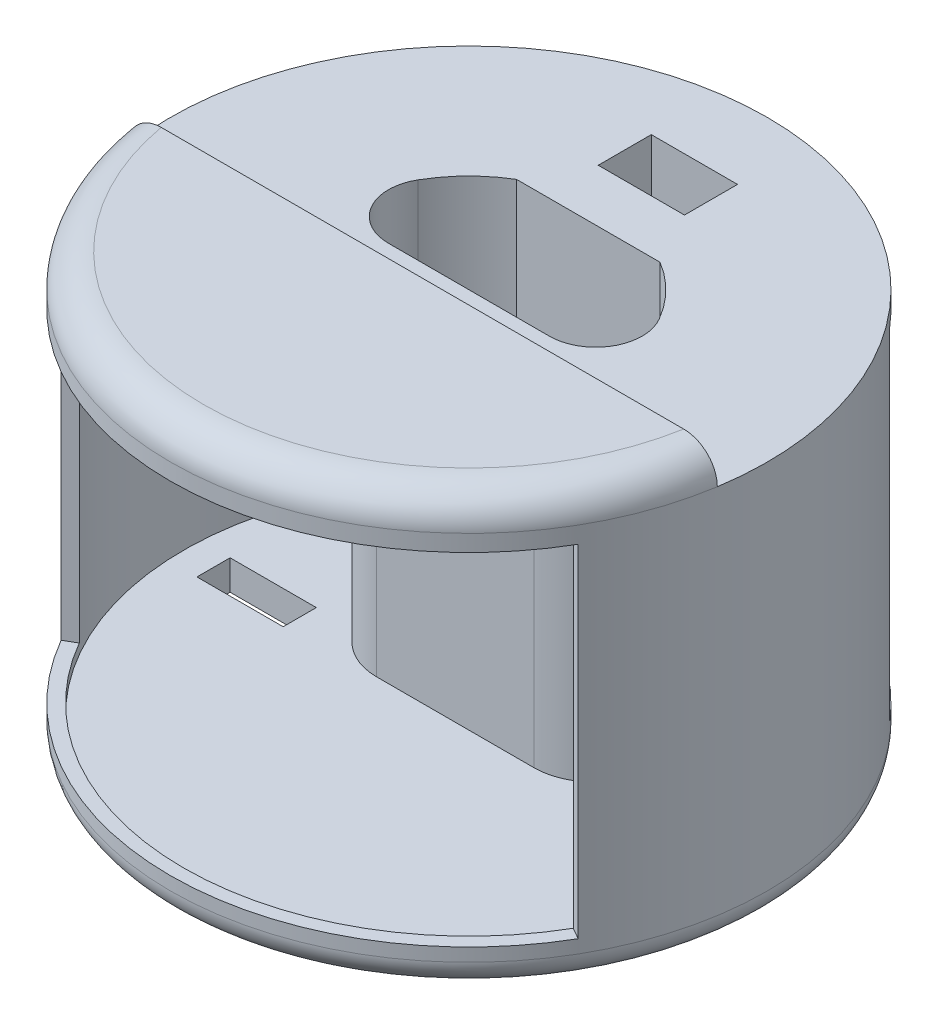
SolidWorks part; units mm, degrees
ref_plane "Front Plane" through (0, 0, 0) normal (0, 0, 1) x (1, 0, 0)
ref_plane "Top Plane" through (0, 0, 0) normal (0, 1, 0) x (1, 0, 0)
ref_plane "Right Plane" through (0, 0, 0) normal (1, 0, 0) x (0, 0, -1)
sketch "Sketch1" plane through (0, 0, 0) normal (0, 0, 1) x (1, 0, 0)
  line L4 (0, 0) -> (0, 76.5) construction
  line L6 (0, 76.5) -> (0, 11.5)
  line L10 (22.5, 0) -> (22.5, 11.5)
  line L11 (22.5, 11.5) -> (0, 11.5)
  line L12 (0, 2) -> (0, 78.1598) construction
  line L13 (25, 11.5) -> (45, 11.5)
  line L15 (22.5, 0) -> (25, 0)
  line L16 (25, 0) -> (25, 11.5)
  line L17 (0, 76.5) -> (40, 76.5)
  line L18 (45, 71.5) -> (45, 11.5)
  arc A3 (45, 71.5) -> (40, 76.5) centre (40, 71.5) ccw
  point P7 (45, 76.5)
  point P8 (45, 11.5)
  point P11 (25, 0)
  point P19 (45, 53.5)
  dimension "D6" = 11.5
  dimension "D7" = 5
  dimension "D1" = 25
  dimension "D2" = 22.5
  dimension "D3" = 11.5
  dimension "D4" = 45
  dimension "D5" = 65
revolve "Revolve1" add sketch "Sketch1" angle 360 about L12
ref_plane "Plane1" through (0, 76.5, 0) normal (0, 1, 0) x (1, 0, 0)
sketch "Sketch5" plane through (0, 76.5, 0) normal (0, 1, 0) x (1, 0, 0)
  line L2 (-45, 0) -> (45, 0)
  arc A1 (45, 0) -> (-45, 0) centre (0, 0) ccw
  dimension "D1" = 45
extrude "Cut-Extrude1" cut sketch "Sketch5" against normal blind 5
ref_plane "Plane3" through (0, 69, 0) normal (0, 1, 0) x (1, 0, 0)
sketch "Sketch7" plane through (0, 11.5, 0) normal (0, -1, 0) x (1, 0, 0)
  line L0 (-21, 0) -> (21, 0)
  line L1 (10.8167, -18) -> (-10.8167, -18)
  arc A0 (-21, 0) -> (21, 0) centre (0, 0) ccw
  circle A2 centre (0, 0) radius 22.5 construction
  dimension "D1" = 21
  dimension "D2" = 1.5
  dimension "D3" = 18
extrude "Cut-Extrude3" cut sketch "Sketch7" against normal blind 60 contours L1 A0 L0
sketch "Sketch8" plane through (0, 69, 0) normal (0, 1, 0) x (1, 0, 0)
  line L0 (-37, 0) -> (37, 0) construction
  line L1 (22.9129, -2) -> (-22.9816, -2)
  line L3 (-10.5739, 20) -> (10.5052, 20)
  circle A0 centre (0, 0) radius 43
  arc A3 (-22.9816, -2) -> (-10.5739, 20) centre (-0.0344, -0.4431) cw
  arc A4 (45, 0) -> (-45, 0) centre (0, 0) ccw construction
  arc A6 (10.5052, 20) -> (22.9129, -2) centre (-0.0344, -0.4431) cw
  dimension "D1" = 2
  dimension "D2" = 22
extrude "Cut-Extrude4" cut sketch "Sketch8" against normal blind 53
ref_plane "Plane4" through (0, 17.5, 0) normal (0, 1, 0) x (1, 0, 0)
ref_plane "Plane5" through (0, 2, 0) normal (0, -1, 0) x (-1, 0, 0)
ref_plane "Plane7" through (0, 5.5, 0) normal (0, -1, 0) x (-1, 0, 0)
fillet "Fillet1" radius 7 2 edges at (21, 41.5, 0) (-21, 41.5, 0)
sketch "Sketch12" plane through (0, 0, 0) normal (1, 0, 0) x (0, 0, -1)
  line L0 (47.3, 17.5) -> (-47.3, 17.5) construction
  line L1 (-48, 69) -> (-41.5, 69)
  line L2 (-48, 69) -> (-48, 17.5)
  line L3 (-48, 17.5) -> (-41.5, 17.5)
  line L4 (-41.5, 69) -> (-41.5, 17.5)
  line L6 (0, 71.5) -> (-45, 71.5) construction
  line L8 (0, 71.5) -> (0, 11.5) construction
  dimension "D1" = 2.5
  dimension "D2" = 6.5
  dimension "D3" = 48
revolve "Cut-Revolve1" cut sketch "Sketch12" angle 60
sketch "Sketch18" plane through (0, 71.5, 0) normal (0, 1, 0) x (1, 0, 0)
  line L0 (-45, 0) -> (-12.1244, 0) construction
  line L1 (-6.5, 34) -> (6.5, 34)
  line L2 (-6.5, 34) -> (-6.5, 26)
  line L3 (-6.5, 26) -> (6.5, 26)
  line L4 (6.5, 34) -> (6.5, 26)
  line L5 (-6.5, 34) -> (6.5, 26) construction
  line L6 (-6.5, 26) -> (6.5, 34) construction
  point P0 (0, 30)
  dimension "D1" = 8
  dimension "D2" = 13
  dimension "D3" = 30
  dimension "D4" = 45
extrude "Cut-Extrude13" cut sketch "Sketch18" against normal blind 5
sketch "Sketch20" plane through (0, 76.5, 0) normal (0, 1, 0) x (1, 0, 0)
  line L1 (50, 0) -> (-50, 0)
  line L2 (50, 0) -> (50, -7)
  line L3 (50, -7) -> (-50, -7)
  line L4 (-50, 0) -> (-50, -7)
  dimension "D1" = 7
  dimension "D2" = 50
  dimension "D3" = 50
extrude "Cut-Extrude15" cut sketch "Sketch20" against normal blind 5
sketch "Sketch19" plane through (0, 0, 7) normal (0, 0, -1) x (-1, 0, 0)
  line L0 (0, 70.6176) -> (0, 16.2649) construction
  line L1 (22, 76.5) -> (-22, 76.5) construction
  circle A0 centre (0, 74) radius 1.5
  circle A1 centre (-30, 74) radius 1.5
  circle A2 centre (29.4522, 74) radius 1.5
  dimension "D1" = 3
  dimension "D7" = 3
  dimension "D8" = 3
  dimension "D2" = 2.5
  dimension "D3" = 15
  dimension "D4" = 15
  dimension "D5" = 2.5
  dimension "D6" = 2.5
extrude "Cut-Extrude14" cut sketch "Sketch19" against normal blind 12
fillet "Fillet3" radius 4 1 edges at (0, 11.5, -45)
ref_plane "Plane8" through (0, 14.5, 0) normal (0, 1, 0) x (1, 0, 0)
sketch "Sketch24" plane through (0, 0, 0) normal (0, -1, 0) x (1, 0, 0)
  line L1 (-1, -21) -> (1, -21)
  line L2 (-1, -21) -> (-1, -24)
  line L3 (-1, -24) -> (1, -24)
  line L4 (1, -21) -> (1, -24)
  line L5 (0, -24) -> (0, -21) construction
  line L6 (-1, -22.5) -> (1, -22.5) construction
  circle A0 centre (0, 0) radius 22.5 construction
  circle A1 centre (0, 0) radius 22.5 construction
  point P0 (0, -22.5)
  dimension "D1" = 3
  dimension "D2" = 2
extrude "Boss-Extrude3" add sketch "Sketch24" against normal blind 2
pattern_circular "CirPattern2" count 5 over 360 about axis through (0, 0, 0) along (0, 1, 0) of "Boss-Extrude3"
sketch "Sketch26" plane through (0, 0, 0) normal (1, 0, 0) x (0, 0, -1)
  line L0 (24.75, 69) -> (-24.75, 69) construction
  line L1 (42.5569, 69) -> (47.5569, 69)
  line L2 (42.5569, 69) -> (42.5569, 17.5)
  line L3 (42.5569, 17.5) -> (47.5569, 17.5)
  line L4 (47.5569, 69) -> (47.5569, 17.5)
  line L5 (47.3, 17.5) -> (-47.3, 17.5) construction
  line L7 (-0.4431, 16) -> (-0.4431, 69) construction
  dimension "D1" = 5
  dimension "D2" = 43
revolve "Cut-Revolve2" cut sketch "Sketch26" angle 50 about axis through (0, 2, 0) along (0, -1, 0) other way angle 50
sketch "Sketch27" plane through (0, 0, 0) normal (0.5, 0, 0.866) x (0.866, 0, -0.5)
sketch "Sketch28" plane through (0, 0, 0) normal (-0.6428, 0, -0.766) x (-0.766, 0, 0.6428)
sketch "Sketch29" plane through (0, 69, 0) normal (0, -1, 0) x (1, 0, 0)
  line L0 (6.5, -26) -> (6.5, -34) construction
  line L1 (8.1, -35.6) -> (-8.1, -35.6)
  line L2 (8.1, -35.6) -> (8.1, -24.4)
  line L3 (8.1, -24.4) -> (-8.1, -24.4)
  line L4 (-8.1, -35.6) -> (-8.1, -24.4)
  line L5 (-6.5, -34) -> (-6.5, -26) construction
  line L6 (6.5, -34) -> (-6.5, -34) construction
  line L7 (-6.5, -26) -> (6.5, -26) construction
  line L8 (6.5, -34) -> (6.5, -26)
  line L9 (6.5, -26) -> (-6.5, -26)
  line L10 (-6.5, -34) -> (-6.5, -26)
  line L11 (6.5, -34) -> (-6.5, -34)
  dimension "D1" = 1.6
  dimension "D2" = 1.6
  dimension "D3" = 1.6
  dimension "D4" = 1.6
  dimension "D5" = 1.6
extrude "Boss-Extrude4" add sketch "Sketch29" along normal blind 19
sketch "Sketch36" plane through (0, 0, -35.6) normal (0, 0, -1) x (-1, 0, 0)
  line L1 (-7.1596, 38.9181) -> (-5.1596, 38.9181)
  line L2 (-7.1596, 38.9181) -> (-7.1596, 36.9181)
  line L3 (-7.1596, 36.9181) -> (-5.1596, 36.9181)
  line L4 (-5.1596, 38.9181) -> (-5.1596, 36.9181)
  line L5 (-6.1596, 36.9181) -> (-6.1596, 38.9181) construction
  line L6 (-7.1596, 37.9181) -> (-5.1596, 37.9181) construction
  point P0 (-6.1596, 37.9181)
  point P4 (-6.1596, 37.9181)
  point P5 (6.0515, 37.9181)
  dimension "D1" = 2
  dimension "D2" = 2
extrude "Boss-Extrude7" add sketch "Sketch36" along normal blind 5
sketch "Sketch37" plane through (5.1596, 0, 0) normal (-1, 0, 0) x (0, 0, 1)
  line L0 (-40.6, 36.9181) -> (-35.6, 36.9181) construction
  line L1 (-40.5974, 38.9181) -> (-38.5974, 38.9181)
  line L2 (-40.5974, 38.9181) -> (-40.5974, 36.9181)
  line L3 (-40.5974, 36.9181) -> (-38.5974, 36.9181)
  line L4 (-38.5974, 38.9181) -> (-38.5974, 36.9181)
  line L5 (-39.5974, 36.9181) -> (-39.5974, 38.9181) construction
  line L6 (-40.5974, 37.9181) -> (-38.5974, 37.9181) construction
  point P0 (-39.5974, 37.9181)
  dimension "D1" = 2
  dimension "D2" = 2
extrude "Boss-Extrude8" add sketch "Sketch37" along normal blind 12.5
sketch "Sketch39" plane through (0, 0, -40.6) normal (0, 0, -1) x (-1, 0, 0)
  line L0 (-5.1596, 38.9181) -> (-7.1596, 38.9181) construction
  line L1 (-7.1596, 38.9181) -> (-7.1596, 36.9181) construction
  point P0 (-6.1596, 37.9181)
  dimension "D1" = 1
  dimension "D2" = 1
sketch "Sketch40" plane through (0, 0, -35.6) normal (0, 0, -1) x (-1, 0, 0)
  line L1 (5.3404, 38.9181) -> (7.3404, 38.9181)
  line L2 (5.3404, 38.9181) -> (5.3404, 36.9181)
  line L3 (5.3404, 36.9181) -> (7.3404, 36.9181)
  line L4 (7.3404, 38.9181) -> (7.3404, 36.9181)
  line L5 (6.3404, 36.9181) -> (6.3404, 38.9181) construction
  line L6 (5.3404, 37.9181) -> (7.3404, 37.9181) construction
  point P0 (6.3404, 37.9181)
  point P1 (-6.1596, 37.9181)
  point P2 (6.3404, 37.9181)
  point P4 (6.3404, 37.9181)
  dimension "D1" = 2
  dimension "D2" = 2
  dimension "D3" = 12.5
extrude "Boss-Extrude9" add sketch "Sketch40" along normal blind 5
ref_plane "Plane10" through (0, 0, -35.6) normal (0, 0, -1) x (-1, 0, 0)
ref_plane "Plane12" through (0, 66, 0) normal (0, -1, 0) x (-1, 0, 0)
sketch "Sketch49" plane through (0, 66, 0) normal (0, -1, 0) x (-1, 0, 0)
  line L1 (4.7002, 32.5398) -> (-5.2998, 32.5398)
  line L2 (4.7002, 32.5398) -> (4.7002, 27.5398)
  line L3 (4.7002, 27.5398) -> (-5.2998, 27.5398)
  line L4 (-5.2998, 32.5398) -> (-5.2998, 27.5398)
  line L5 (-0.2998, 27.5398) -> (-0.2998, 32.5398) construction
  line L6 (4.7002, 30.0398) -> (-5.2998, 30.0398) construction
  point P0 (-0.2998, 30.0398)
  dimension "D1" = 5
  dimension "D2" = 10
fillet "Fillet8" radius 9 2 edges at (22.9129, 42.5, 2) (-22.9816, 42.5, 2)
ref_plane "Plane14" through (0, 16, 0) normal (0, 1, 0) x (1, 0, 0)
sketch "Sketch50" plane through (0, 16, 0) normal (0, 1, 0) x (1, 0, 0)
  line L0 (0, -42.075) -> (0, 42.075) construction
  line L1 (-25.5, -2.5) -> (-38.5, -2.5)
  line L2 (-25.5, -2.5) -> (-25.5, 2.5)
  line L3 (-25.5, 2.5) -> (-38.5, 2.5)
  line L4 (-38.5, -2.5) -> (-38.5, 2.5)
  line L5 (-32, 2.5) -> (-32, -2.5) construction
  line L6 (-25.5, 0) -> (-38.5, 0) construction
  line L7 (25.5, -2.5) -> (38.5, -2.5)
  line L8 (38.5, -2.5) -> (38.5, 2.5)
  line L9 (25.5, -2.5) -> (25.5, 2.5)
  line L10 (25.5, 2.5) -> (38.5, 2.5)
  line L11 (38.5, -2.5) -> (38.5, 2.5)
  line L12 (25.5, 2.5) -> (38.5, 2.5)
  line L13 (25.5, -2.5) -> (25.5, 2.5)
  line L14 (25.5, -2.5) -> (38.5, -2.5)
  point P0 (-32, 0)
  dimension "D1" = 13
  dimension "D2" = 5
  dimension "D3" = 32
extrude "Cut-Extrude23" cut sketch "Sketch50" against normal blind 7 contours L10 L9 L7 L8 | L3 L4 L1 L2
